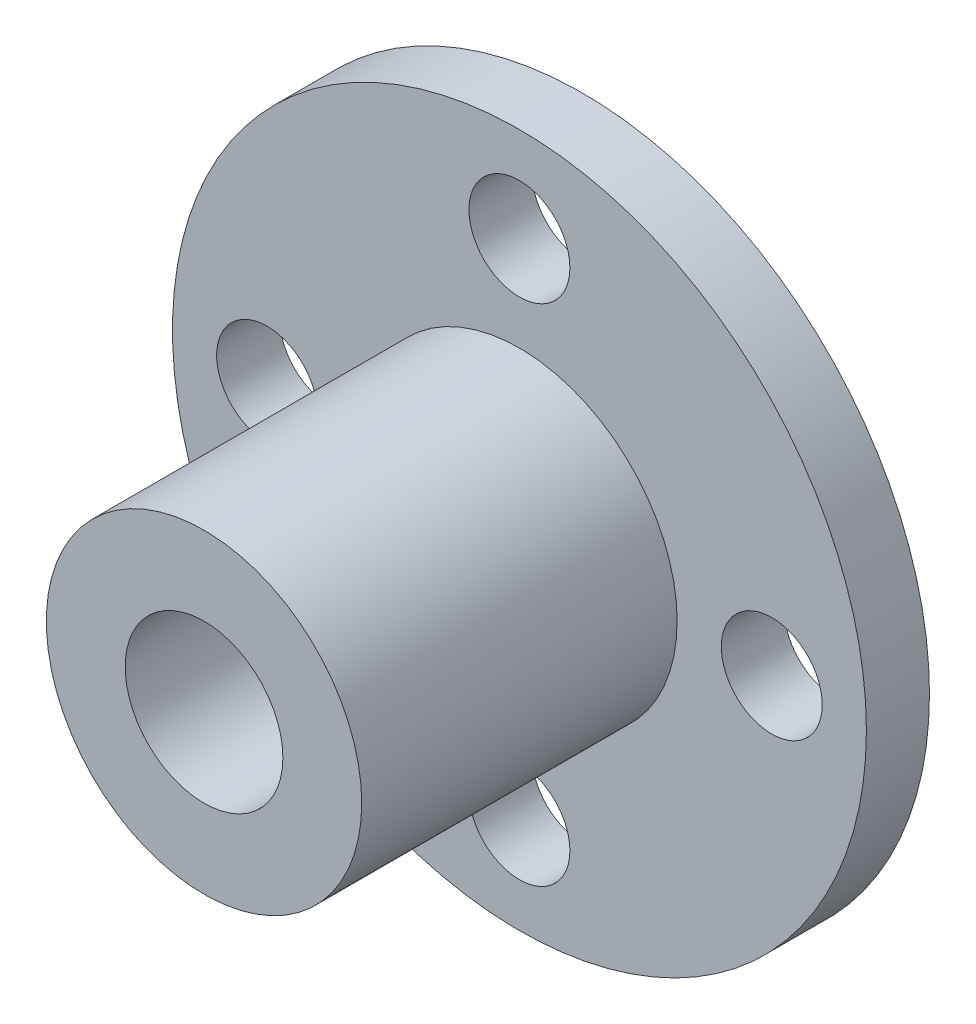
SolidWorks part; units mm, degrees
material "AISI 1045 钢，冷拔"
ref_plane "前视基准面" through (0, 0, 0) normal (0, 0, 1) x (1, 0, 0)
ref_plane "上视基准面" through (0, 0, 0) normal (0, 1, 0) x (1, 0, 0)
ref_plane "右视基准面" through (0, 0, 0) normal (1, 0, 0) x (0, 0, -1)
sketch "草图1" plane through (0, 0, 0) normal (0, 0, 1) x (1, 0, 0)
  circle A0 centre (0, 0) radius 11
  dimension "D1" = 22
extrude "凸台-拉伸1" add sketch "草图1" along normal blind 2
sketch "草图2" plane through (0, 0, 2) normal (0, 0, 1) x (1, 0, 0)
  circle A0 centre (0, 0) radius 5
  dimension "D1" = 10
extrude "凸台-拉伸2" add sketch "草图2" along normal blind 10
sketch "草图3" plane through (0, 0, 12) normal (0, 0, 1) x (1, 0, 0)
  circle A0 centre (0, 0) radius 2.5
  dimension "D1" = 5
extrude "切除-拉伸1" cut sketch "草图3" against normal through all
hole_wizard "Ø3.2 (3.2) 直径孔1" positions "草图5" profile "草图4" hole size "Ø3.2" standard "GB"
sketch "草图5" plane through (0, 0, 2) normal (0, 0, 1) x (1, 0, 0)
  circle A0 centre (0, 0) radius 8 construction
  point P16 (8, 0)
  point P17 (-8, 0)
  point P19 (0, -8)
  point P21 (0, 8)
  dimension "D1" = 16
sketch "草图4" plane through (8, 0, 2) normal (1, 0, 0) x (0, -1, 0)
  line L0 (0, 0) -> (0, 10.9614)
  line L1 (0, 10.9614) -> (1.6, 10)
  line L2 (1.6, 10) -> (1.6, 0)
  line L5 (1.6, 0) -> (0, 0)
  line L10 (0, 10.9614) -> (-1.6, 10) construction
  line L11 (0, -6.35) -> (0, 107.95) construction
  dimension "孔直径" = 3.2
  dimension "孔深度" = 10
  dimension "导头角度" = 118
